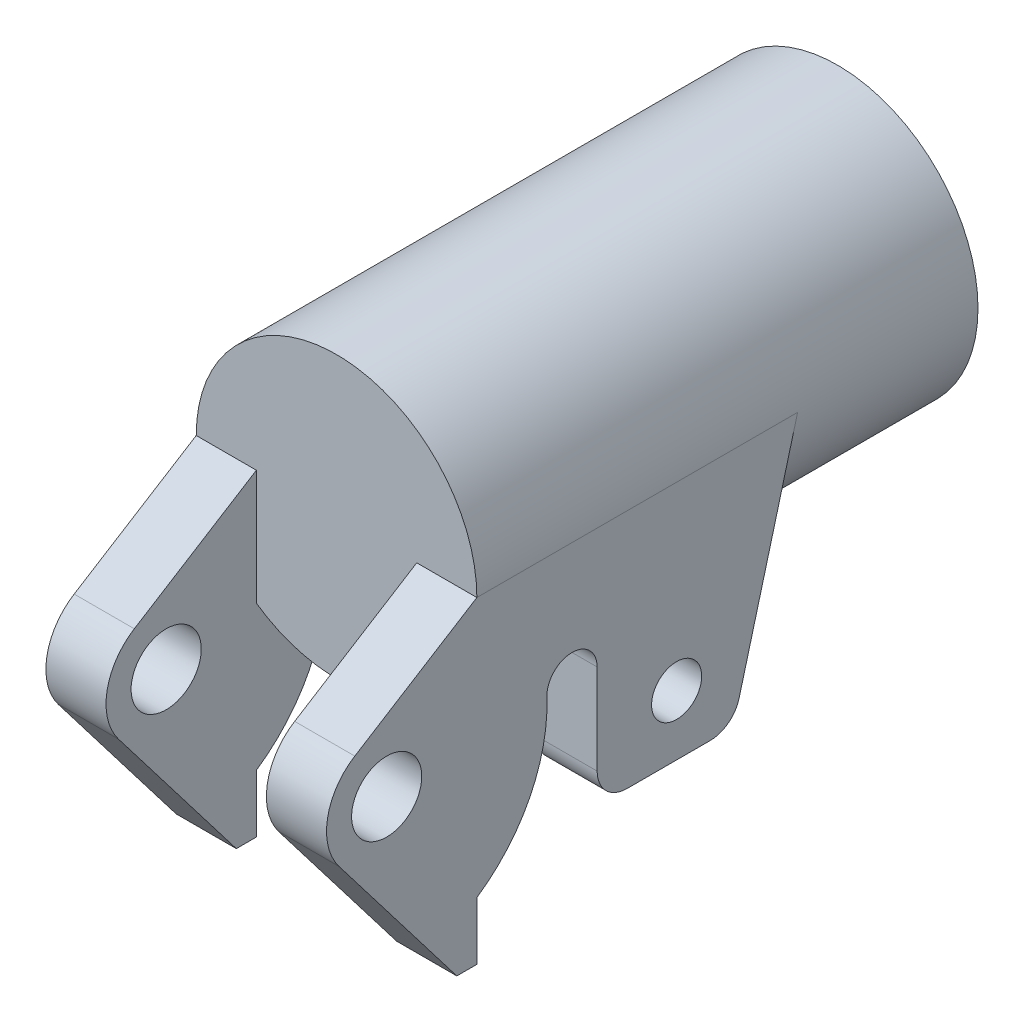
SolidWorks part; units mm, degrees
ref_plane "Front Plane" through (0, 0, 0) normal (0, 0, 1) x (1, 0, 0)
ref_plane "Top Plane" through (0, 0, 0) normal (0, 1, 0) x (1, 0, 0)
ref_plane "Right Plane" through (0, 0, 0) normal (1, 0, 0) x (0, 0, -1)
sketch "Sketch1" plane through (0, 0, 0) normal (0, 0, 1) x (1, 0, 0)
  circle A0 centre (0, 0) radius 14
  dimension "D1" = 28
extrude "Boss-Extrude1" add sketch "Sketch1" against normal blind 50
sketch "Sketch2" plane through (0, 0, 0) normal (1, 0, 0) x (0, 0, -1)
  line L0 (0, 0) -> (-12.1795, -7.6106)
  line L1 (0, 14) -> (0, -14) construction
  line L2 (-13.7626, -16.3483) -> (-2, -31.6989)
  line L3 (-2, -31.6989) -> (0, -31.6989)
  line L4 (0, -31.6989) -> (0, -25.9277)
  line L5 (12, -12) -> (12, -21)
  line L6 (15, -24) -> (23.2672, -24)
  line L7 (26.165, -21.7765) -> (32, 0)
  line L8 (0, 0) -> (32, 0)
  line L9 (32, 0) -> (32, -19.7199) construction
  arc A0 (-12.1795, -7.6106) -> (-13.7626, -16.3483) centre (-9, -12.6989) ccw
  arc A1 (0, -25.9277) -> (6.9886, -12.0947) centre (-9, -12.6989) ccw
  arc A2 (6.9886, -12.0947) -> (12, -12) centre (9.4934, -12) cw
  circle A3 centre (-9, -12.6989) radius 3.5
  circle A4 centre (19.93, -18) radius 2.5
  arc A5 (15, -24) -> (12, -21) centre (15, -21) cw
  arc A6 (23.2672, -24) -> (26.165, -21.7765) centre (23.2672, -21) ccw
  point P4 (-2, -33.9077)
  point P17 (0, 0)
  point P25 (20.2102, -13.4241)
  point P26 (0, 0)
  point P27 (14.4055, -12)
  point P28 (10.6966, -12.1315)
  point P30 (15.1677, -12)
  point P31 (0, 0)
  point P32 (0, 0)
  point P33 (0, 0)
  point P34 (0, 0)
  point P35 (0, 0)
  dimension "D1" = 3
  dimension "D2" = 3
  dimension "D7" = 7
  dimension "D8" = 6
  dimension "D10" = 16
  dimension "D11" = 5
  dimension "D3" = 7
  dimension "D4" = 12
  dimension "D5" = 9
  dimension "D6" = 32
  dimension "D9" = 2
  dimension "D12" = 15
  dimension "D13" = 6
  dimension "D14" = 19
  dimension "D15" = 32
  dimension "D16" = 24
  dimension "D18" = 20
extrude "Boss-Extrude2" add sketch "Sketch2" along normal mid plane 28 contours L6 A6 L7 L8 L0 A0 L2 L3 L4 A1 A2 L5 A5 A3 A4
sketch "Sketch4" plane through (0, 0, 0) normal (0, 0, 1) x (1, 0, 0)
  line L4 (-8, -31.6989) -> (-8, -11.4891)
  line L5 (-8, -31.6989) -> (8, -31.6989)
  line L9 (8, -31.6989) -> (8, -11.4891)
  arc A0 (-8, -11.4891) -> (8, -11.4891) centre (0, 0) ccw
extrude "Cut-Extrude3" cut sketch "Sketch4" against normal through all both and the other way through all contours A0 L9 L5 L4
sketch "Sketch5" plane through (0, 0, 0) normal (0, 0, 1) x (1, 0, 0)
  line L0 (14, 0) -> (-14, 0) construction
  line L1 (-8, 0) -> (8, 0)
  line L2 (-14, -31.6989) -> (-8, -31.6989)
  line L3 (-14, -31.6989) -> (-14, 0)
  line L5 (-8, -11.4891) -> (-8, 0)
  line L6 (14, -31.6989) -> (8, -31.6989)
  line L9 (8, -11.4891) -> (8, 0)
  arc A0 (-8, -11.4891) -> (8, -11.4891) centre (0, 0) ccw
  dimension "D1" = 6
  dimension "D2" = 6
extrude "Cut-Extrude4" cut sketch "Sketch5" along normal blind 57 contours A0 L9 L1 L5
sketch "Sketch6" plane through (0, 0, -50) normal (0, 0, -1) x (-1, 0, 0)
  circle A0 centre (0, 0) radius 11
  dimension "D1" = 22
extrude "Cut-Extrude5" cut sketch "Sketch6" against normal blind 40
